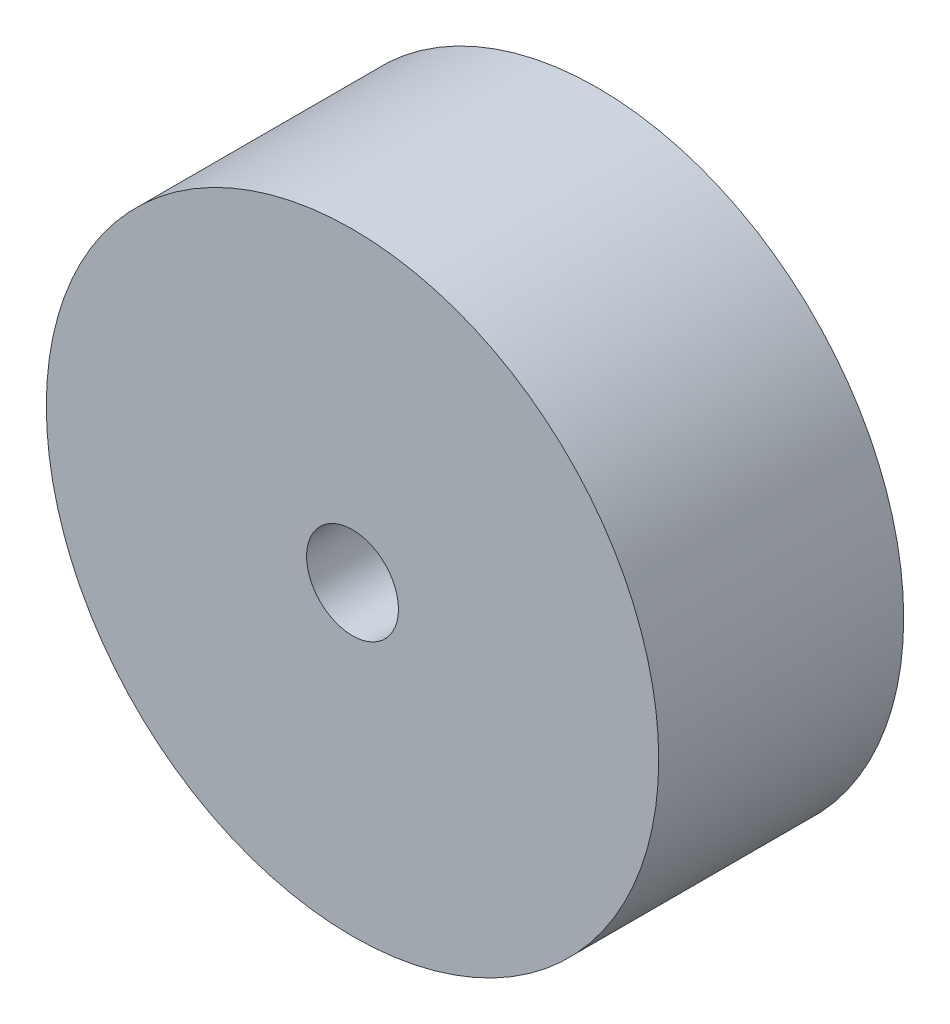
SolidWorks part; units mm, degrees
material "Beech"
ref_plane "Front" through (0, 0, 0) normal (0, 0, 1) x (1, 0, 0)
ref_plane "Top" through (0, 0, 0) normal (0, 1, 0) x (1, 0, 0)
ref_plane "Right" through (0, 0, 0) normal (1, 0, 0) x (0, 0, -1)
sketch "Sketch1" plane through (0, 0, 0) normal (0, 0, 1) x (1, 0, 0)
  circle A0 centre (0, 0) radius 1.5
  circle A1 centre (0, 0) radius 10
  dimension "D1" = 3
  dimension "D2" = 8.5
extrude "Boss-Extrude1" add sketch "Sketch1" along normal blind 8
